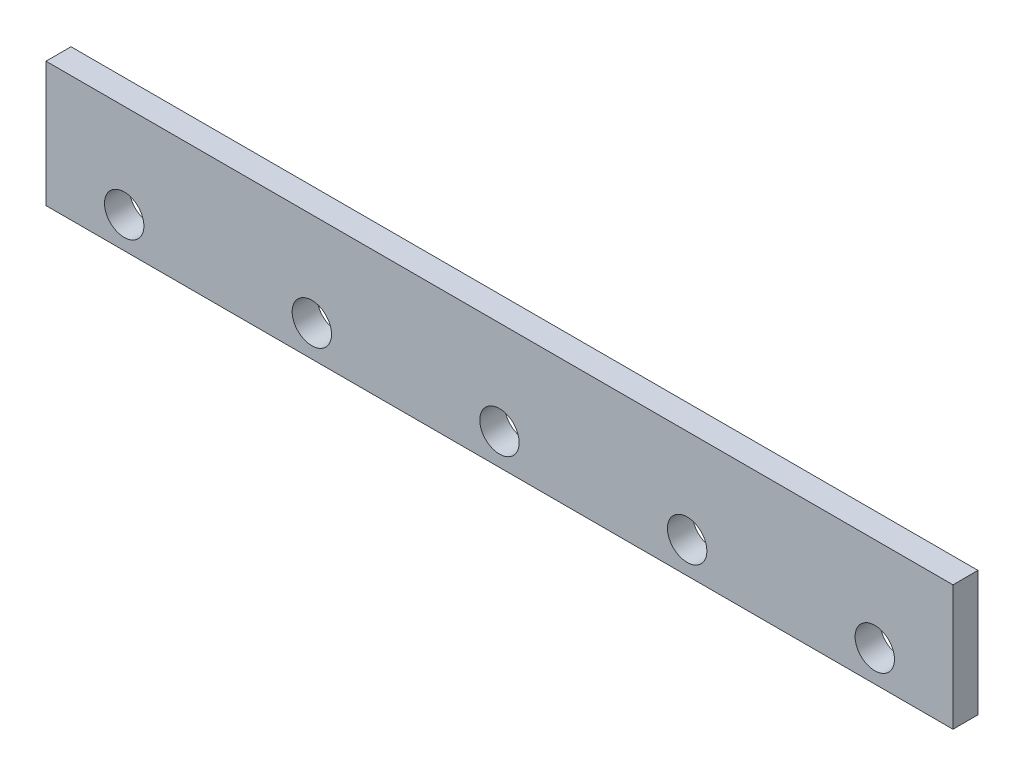
SolidWorks part; units mm, degrees
ref_plane "Alzado" through (0, 0, 0) normal (0, 0, 1) x (1, 0, 0)
ref_plane "Planta" through (0, 0, 0) normal (0, 1, 0) x (1, 0, 0)
ref_plane "Vista lateral" through (0, 0, 0) normal (1, 0, 0) x (0, 0, -1)
sketch "Croquis1" plane through (0, 0, 0) normal (0, 0, 1) x (1, 0, 0)
  line L0 (0, 0) -> (-580, 0)
  line L1 (-580, 0) -> (-580, 80)
  line L2 (-580, 80) -> (0, 80)
  line L3 (0, 80) -> (0, 0)
  line L4 (-580, 20) -> (0, 20) construction
  circle A0 centre (-530, 20) radius 12.6
  circle A1 centre (-410, 20) radius 12.6
  circle A2 centre (-290, 20) radius 12.6
  circle A3 centre (-170, 20) radius 12.6
  circle A4 centre (-50, 20) radius 12.6
  dimension "D5" = 25.2
  dimension "D1" = 580
  dimension "D2" = 80
  dimension "D3" = 20
  dimension "D4" = 50
  dimension "D7" = 120
  dimension "D6" = 5
extrude "Saliente-Extruir1" add sketch "Croquis1" against normal blind 16
